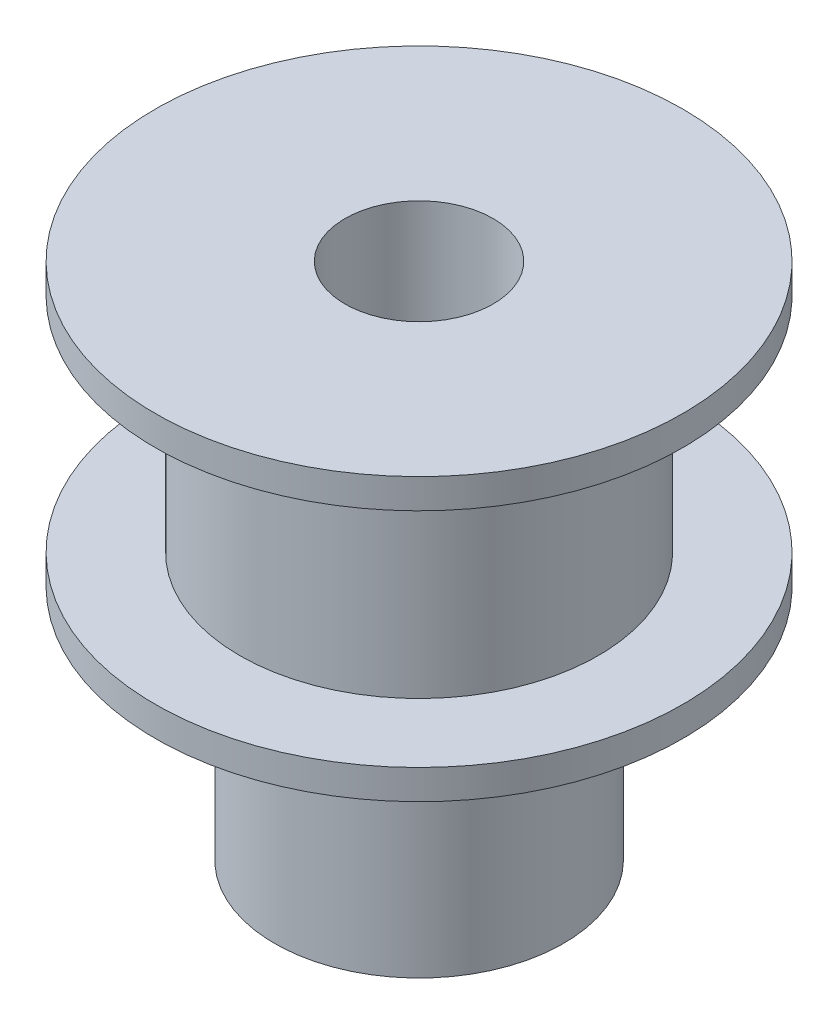
SolidWorks part; units mm, degrees
ref_plane "Front Plane" through (0, 0, 0) normal (0, 0, 1) x (1, 0, 0)
ref_plane "Top Plane" through (0, 0, 0) normal (0, 1, 0) x (1, 0, 0)
ref_plane "Right Plane" through (0, 0, 0) normal (1, 0, 0) x (0, 0, -1)
sketch "Sketch1" plane through (0, 0, 0) normal (0, 0, 1) x (1, 0, 0)
  line L0 (-2.5, 0) -> (-2.5, 17.5)
  line L1 (-2.5, 17.5) -> (-8.9, 17.5)
  line L2 (-8.9, 17.5) -> (-8.9, 16.5)
  line L3 (-8.9, 16.5) -> (-6.05, 16.5)
  line L4 (-6.05, 16.5) -> (-6.05, 9)
  line L5 (-6.05, 9) -> (-8.9, 9)
  line L6 (-8.9, 9) -> (-8.9, 8)
  line L7 (-8.9, 8) -> (-4.875, 8)
  line L8 (-4.875, 8) -> (-4.875, 0)
  line L9 (-4.875, 0) -> (-2.5, 0)
  line L10 (0, 0) -> (0, 23.1903) construction
  line L11 (0, 0) -> (-4.875, 0) construction
  dimension "D1" = 17.5
  dimension "D2" = 5
  dimension "D3" = 12.1
  dimension "D4" = 9.75
  dimension "D5" = 17.8
  dimension "D6" = 1
  dimension "D7" = 1
  dimension "D8" = 9.5
revolve "Revolve1" add sketch "Sketch1" angle 360 about L10
